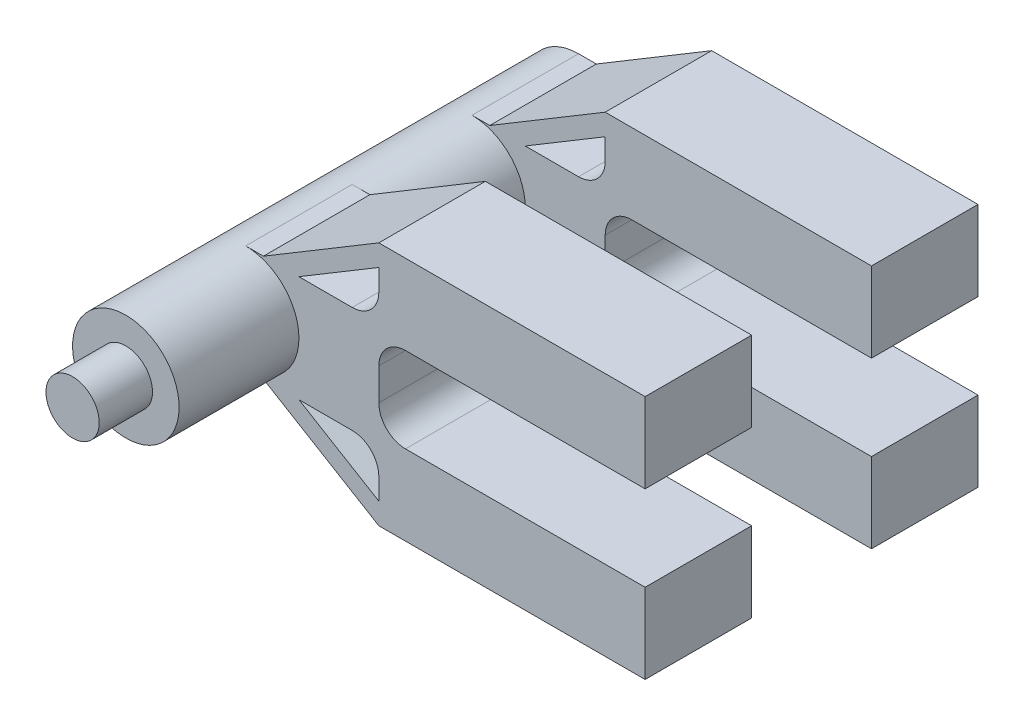
SolidWorks part; units mm, degrees
ref_plane "정면" through (0, 0, 0) normal (0, 0, 1) x (1, 0, 0)
ref_plane "윗면" through (0, 0, 0) normal (0, 1, 0) x (1, 0, 0)
ref_plane "우측면" through (0, 0, 0) normal (1, 0, 0) x (0, 0, -1)
sketch "스케치1" plane through (0, 0, 0) normal (0, 0, 1) x (1, 0, 0)
  circle A0 centre (0, 0) radius 20
  dimension "D1" = 40
extrude "보스-돌출1" add sketch "스케치1" along normal blind 170
sketch "스케치2" plane through (0, 0, 0) normal (1, 0, 0) x (0, 0, -1)
  line L0 (-170, -20) -> (0, -20) construction
  line L1 (0, 20) -> (-40, 20)
  line L2 (0, 20) -> (0, -20)
  line L3 (0, -20) -> (-40, -20)
  line L4 (-40, 20) -> (-40, -20)
  line L5 (0, 20) -> (-170, 20) construction
  line L6 (-85, 20) -> (-125, 20)
  line L7 (-85, 20) -> (-85, -20)
  line L8 (-85, -20) -> (-125, -20)
  line L9 (-125, 20) -> (-125, -20)
extrude "보스-돌출2" add sketch "스케치2" along normal blind 50
sketch "스케치3" plane through (0, 0, 0) normal (0, 0, -1) x (-1, 0, 0)
  line L0 (-50, -20) -> (-50, 20) construction
  line L1 (-50, -46) -> (-150, -46)
  line L2 (-50, -46) -> (-50, -16)
  line L3 (-50, -16) -> (-150, -16)
  line L4 (-150, -46) -> (-150, -16)
  line L5 (-50, 16) -> (-150, 16)
  line L6 (-50, 16) -> (-50, 46)
  line L7 (-50, 46) -> (-150, 46)
  line L8 (-150, 16) -> (-150, 46)
  line L9 (-50, 20) -> (0, 20) construction
  point P10 (-50, 0)
  dimension "D1" = 32
  dimension "D2" = 20
  dimension "D3" = 16
  dimension "D4" = 100
  dimension "D5" = 100
  dimension "D6" = 30
  dimension "D7" = 30
extrude "보스-돌출3" add sketch "스케치3" against normal blind 40
sketch "스케치4" plane through (0, 0, 85) normal (0, 0, -1) x (-1, 0, 0)
  line L0 (-50, -46) -> (-150, -46)
  line L1 (-50, -46) -> (-50, -16)
  line L2 (-50, -16) -> (-150, -16)
  line L3 (-150, -46) -> (-150, -16)
  line L4 (-50, 16) -> (-150, 16)
  line L5 (-50, 16) -> (-50, 46)
  line L6 (-50, 46) -> (-150, 46)
  line L7 (-150, 16) -> (-150, 46)
  line L8 (-50, -16) -> (-50, 16) construction
  point P14 (-50, 0)
  dimension "D1" = 32
  dimension "D3" = 100
  dimension "D4" = 100
  dimension "D5" = 30
  dimension "D6" = 30
  dimension "D7" = 16
extrude "보스-돌출4" add sketch "스케치4" against normal blind 40
fillet "필렛1" radius 10 8 edges at (50, -16, 105) (50, -20, 105) (50, -20, 20) (50, -16, 20) (50, 16, 105) (50, 16, 20) (50, 20, 105) (50, 20, 20)
ref_plane "평면1" through (0, 0, 20) normal (0, 0, 1) x (1, 0, 0)
sketch "스케치10" plane through (0, 0, 170) normal (0, 0, 1) x (1, 0, 0)
  circle A0 centre (0, 0) radius 10
  dimension "D1" = 20
sketch "스케치11" plane through (0, 0, 20) normal (0, 0, 1) x (1, 0, 0)
  line L0 (20, 20) -> (50, 38)
  line L1 (40, 20) -> (0, 20) construction
  line L2 (50, 30) -> (50, 46) construction
  line L3 (50, 46) -> (6.6667, 20)
  line L4 (20, -20) -> (50, -38)
  line L5 (40, -20) -> (0, -20) construction
  line L6 (50, -46) -> (50, -30) construction
  line L7 (6.6667, -20) -> (50, -46)
  line L8 (50, 46) -> (50, 38)
  line L9 (20, 20) -> (6.6667, 20)
  line L10 (20, -20) -> (6.6667, -20)
  line L11 (50, -46) -> (50, -38)
extrude "보스-돌출6" add sketch "스케치11" along normal mid plane 40
ref_plane "평면2" through (0, 0, 105) normal (0, 0, 1) x (1, 0, 0)
sketch "스케치13" plane through (0, 0, 105) normal (0, 0, 1) x (1, 0, 0)
  line L0 (20, 20) -> (50, 38)
  line L1 (40, 20) -> (0, 20) construction
  line L2 (50, 30) -> (50, 46) construction
  line L3 (50, 38) -> (50, 46)
  line L4 (50, 46) -> (6.6667, 20)
  line L5 (6.6667, 20) -> (20, 20)
  line L6 (20, -20) -> (6.6667, -20)
  line L7 (40, -20) -> (0, -20) construction
  line L8 (6.6667, -20) -> (50, -46)
  line L9 (50, -46) -> (50, -38)
  line L10 (50, -46) -> (50, -30) construction
  line L11 (50, -38) -> (20, -20)
extrude "보스-돌출7" add sketch "스케치13" along normal mid plane 40
extrude "보스-돌출8" add sketch "스케치10" along normal blind 20
